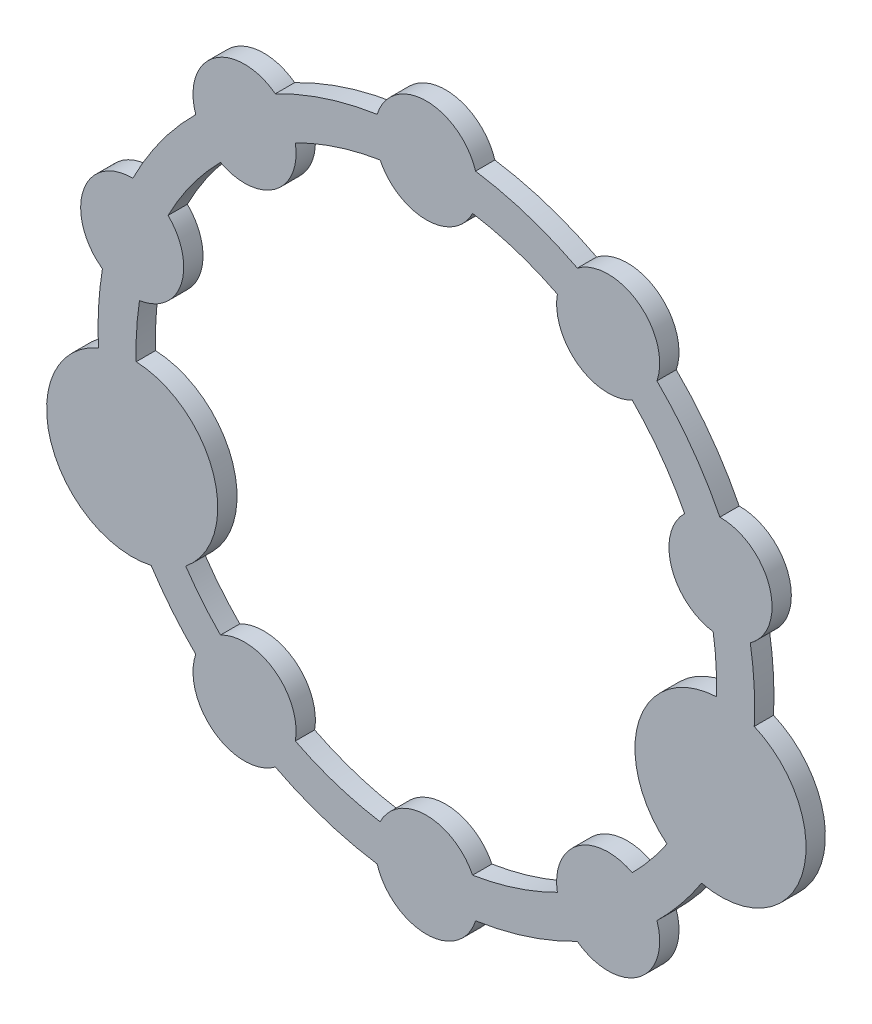
SolidWorks part; units mm, degrees
ref_plane "Front Plane" through (0, 0, 0) normal (0, 0, 1) x (1, 0, 0)
ref_plane "Top Plane" through (0, 0, 0) normal (0, 1, 0) x (1, 0, 0)
ref_plane "Right Plane" through (0, 0, 0) normal (1, 0, 0) x (0, 0, -1)
sketch "Sketch1" plane through (0, 0, 0) normal (0, 0, 1) x (1, 0, 0)
  circle A0 centre (0, -32.53) radius 5.42
  circle A1 centre (0, 0) radius 32.53 construction
  circle A2 centre (-19.1207, -26.3173) radius 5.42
  circle A3 centre (-30.9379, -10.0523) radius 5.42
  circle A4 centre (-30.9379, 10.0523) radius 5.42
  circle A5 centre (-19.1207, 26.3173) radius 5.42
  circle A6 centre (0, 32.53) radius 5.42
  circle A7 centre (19.1207, 26.3173) radius 5.42
  circle A8 centre (30.9379, 10.0523) radius 5.42
  circle A9 centre (30.9379, -10.0523) radius 5.42
  circle A10 centre (19.1207, -26.3173) radius 5.42
  point P25 (0, 0)
  dimension "D1" = 10.84
  dimension "D2" = 65.06
  dimension "D3" = 10
extrude "Boss-Extrude1" add sketch "Sketch1" along normal blind 2.03
sketch "Sketch2" plane through (0, 0, 2.03) normal (0, 0, 1) x (1, 0, 0)
  circle A0 centre (0, 0) radius 30.53
  circle A1 centre (0, 0) radius 34.53
  circle A2 centre (0, 0) radius 32.53 construction
  dimension "D1" = 2
  dimension "D2" = 2
extrude "Boss-Extrude2" add sketch "Sketch2" against normal blind 2.03
sketch "Sketch3" plane through (0, 0, 2.03) normal (0, 0, 1) x (1, 0, 0)
  line L0 (0, 0) -> (-25.7831, -8.3775) construction
  line L1 (-25.7831, -8.3775) -> (-30.9379, -10.0523) construction
  line L2 (-30.9379, -10.0523) -> (-36.0926, -11.7272) construction
  arc A0 (-27.1616, -13.9402) -> (-30.168, -4.6873) centre (-30.9379, -10.0523) ccw construction
  arc A1 (-34.0683, -5.6278) -> (-30.8697, -15.4719) centre (-30.9379, -10.0523) ccw construction
  circle A2 centre (-30.9379, -10.0523) radius 9
  dimension "D1" = 18
extrude "Boss-Extrude3" add sketch "Sketch3" against normal blind 2.03
mirror "Mirror1" about plane through (0, 0, 0) normal (1, 0, 0) of "Boss-Extrude3"
